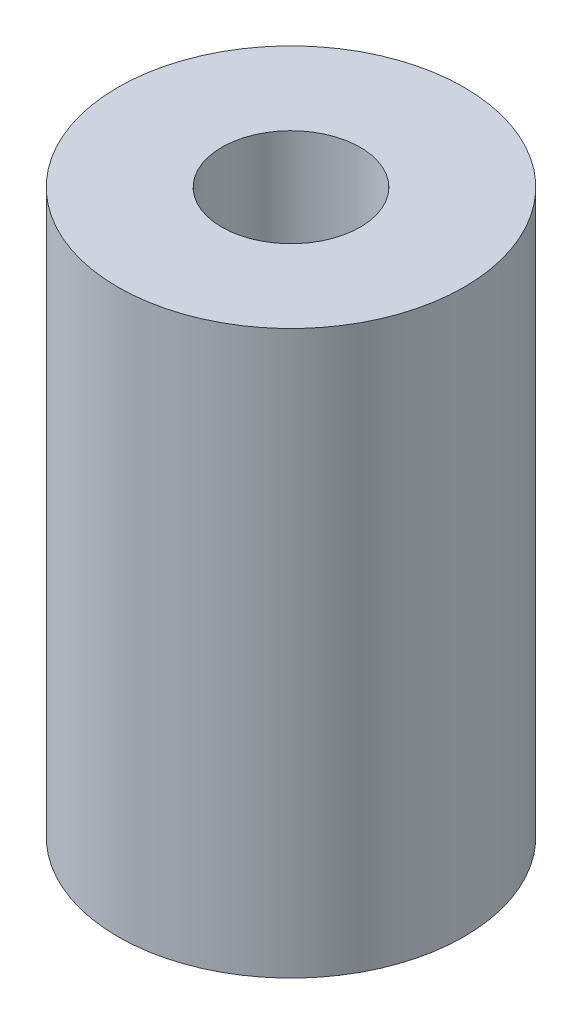
SolidWorks part; units mm, degrees
ref_plane "前视基准面" through (0, 0, 0) normal (0, 0, 1) x (1, 0, 0)
ref_plane "上视基准面" through (0, 0, 0) normal (0, 1, 0) x (1, 0, 0)
ref_plane "右视基准面" through (0, 0, 0) normal (1, 0, 0) x (0, 0, -1)
other "Configuration Table"
sketch "草图1" plane through (0, 0, 0) normal (0, 1, 0) x (1, 0, 0)
  circle A0 centre (0, 0) radius 10
  circle A1 centre (0, 0) radius 2.5
  dimension "D1" = 20
  dimension "D2" = 5
extrude "凸台-拉伸1" add sketch "草图1" along normal blind 15
sketch "草图2" plane through (0, 15, 0) normal (0, 1, 0) x (1, 0, 0)
  circle A0 centre (0, 0) radius 10
  circle A1 centre (0, 0) radius 4
  dimension "D1" = 8
  dimension "D2" = 20
extrude "凸台-拉伸2" add sketch "草图2" along normal blind 17.5
